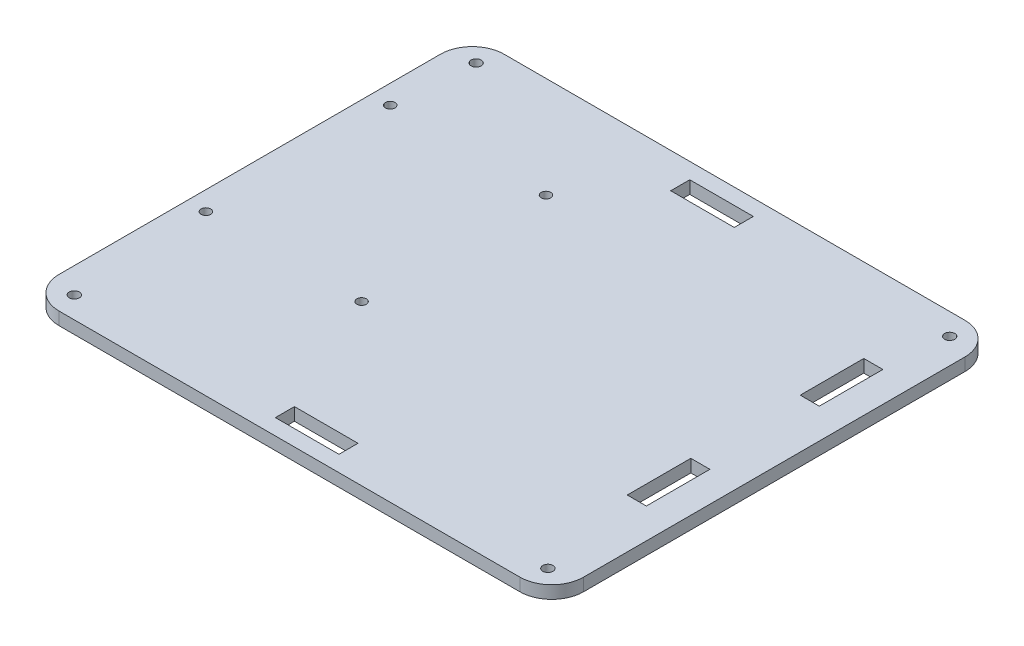
SolidWorks part; units mm, degrees
ref_plane "Front Plane" through (0, 0, 0) normal (0, 0, 1) x (1, 0, 0)
ref_plane "Top Plane" through (0, 0, 0) normal (0, 1, 0) x (1, 0, 0)
ref_plane "Right Plane" through (0, 0, 0) normal (1, 0, 0) x (0, 0, -1)
sketch "Sketch1" plane through (0, 0, 0) normal (0, 1, 0) x (1, 0, 0)
  line L1 (-82.5, 70) -> (82.5, 70)
  line L2 (-82.5, 70) -> (-82.5, -70)
  line L3 (-82.5, -70) -> (82.5, -70)
  line L4 (82.5, 70) -> (82.5, -70)
  line L5 (-82.5, 70) -> (82.5, -70) construction
  line L6 (-82.5, -70) -> (82.5, 70) construction
  point P0 (0, 0)
  dimension "D1" = 165
  dimension "D2" = 140
extrude "Boss-Extrude1" add sketch "Sketch1" along normal blind 4
sketch "Sketch2" plane through (0, 4, 0) normal (0, 1, 0) x (1, 0, 0)
  line L1 (-82.5, 70) -> (82.5, 70) construction
  line L2 (-82.5, 70) -> (-82.5, -70) construction
  line L3 (-82.5, -70) -> (82.5, -70) construction
  line L4 (82.5, 70) -> (82.5, -70) construction
  line L5 (-82.5, 70) -> (82.5, -70) construction
  line L6 (-82.5, -70) -> (82.5, 70) construction
  line L7 (74.5, -63.2121) -> (-74.5, -63.2121) construction
  line L8 (74.5, -63.2121) -> (74.5, 63.2121) construction
  line L9 (74.5, 63.2121) -> (-74.5, 63.2121) construction
  line L10 (-74.5, -63.2121) -> (-74.5, 63.2121) construction
  line L11 (74.5, -63.2121) -> (-74.5, 63.2121) construction
  line L12 (74.5, 63.2121) -> (-74.5, -63.2121) construction
  circle A0 centre (-74.5, 63.2121) radius 1.6
  circle A1 centre (-74.5, -63.2121) radius 1.6
  circle A2 centre (74.5, -63.2121) radius 1.6
  circle A3 centre (74.5, 63.2121) radius 1.6
  point P0 (0, 0)
  point P9 (0, 0)
  dimension "D1" = 3.2
  dimension "D2" = 8
extrude "Cut-Extrude1" cut sketch "Sketch2" against normal blind 10
fillet "Fillet1" radius 10 4 edges at (82.5, 2, -70) (82.5, 2, 70) (-82.5, 2, -70) (-82.5, 2, 70)
sketch "Sketch3" plane through (0, 4, 0) normal (0, 1, 0) x (1, 0, 0)
  line L1 (-80, 41.6892) -> (-24, 41.6892) construction
  line L2 (-80, 41.6892) -> (-80, -43.3108) construction
  line L3 (-80, -43.3108) -> (-24, -43.3108) construction
  line L4 (-24, 41.6892) -> (-24, -43.3108) construction
  line L5 (-80, 41.6892) -> (-24, -43.3108) construction
  line L6 (-80, -43.3108) -> (-24, 41.6892) construction
  line L7 (-76.5, 38.1892) -> (-27.5, 38.1892) construction
  line L8 (-76.5, 38.1892) -> (-76.5, -19.8108) construction
  line L9 (-76.5, -19.8108) -> (-27.5, -19.8108) construction
  line L10 (-27.5, 38.1892) -> (-27.5, -19.8108) construction
  line L11 (-76.5, 38.1892) -> (-27.5, -19.8108) construction
  line L12 (-76.5, -19.8108) -> (-27.5, 38.1892) construction
  circle A0 centre (-76.5, 38.1892) radius 1.5
  circle A1 centre (-27.5, 38.1892) radius 1.5
  circle A2 centre (-76.5, -19.8108) radius 1.5
  circle A3 centre (-27.5, -19.8108) radius 1.5
  point P0 (-52, -0.8108)
  point P5 (-52, 9.1892)
  dimension "D8" = 3
  dimension "D1" = 85
  dimension "D2" = 56
  dimension "D3" = 52
  dimension "D4" = 58
  dimension "D5" = 49
  dimension "D6" = 0
  dimension "D7" = 3.5
extrude "Cut-Extrude2" cut sketch "Sketch3" against normal blind 10
sketch "Sketch4" plane through (0, 4, 0) normal (0, 1, 0) x (1, 0, 0)
  line L1 (67, 43.681) -> (73, 43.681)
  line L2 (67, 43.681) -> (67, 23.681)
  line L3 (67, 23.681) -> (73, 23.681)
  line L4 (73, 43.681) -> (73, 23.681)
  line L5 (67, 43.681) -> (73, 23.681) construction
  line L6 (67, 23.681) -> (73, 43.681) construction
  line L7 (67, -10.7351) -> (73, -10.7351)
  line L8 (67, -10.7351) -> (67, -30.7351)
  line L9 (67, -30.7351) -> (73, -30.7351)
  line L10 (73, -10.7351) -> (73, -30.7351)
  line L11 (67, -10.7351) -> (73, -30.7351) construction
  line L12 (67, -30.7351) -> (73, -10.7351) construction
  line L13 (-9.4499, -59) -> (10.5501, -59)
  line L14 (-9.4499, -59) -> (-9.4499, -65)
  line L15 (-9.4499, -65) -> (10.5501, -65)
  line L16 (10.5501, -59) -> (10.5501, -65)
  line L17 (-9.4499, -59) -> (10.5501, -65) construction
  line L18 (-9.4499, -65) -> (10.5501, -59) construction
  line L19 (-9.0694, 65) -> (10.9306, 65)
  line L20 (-9.0694, 65) -> (-9.0694, 59)
  line L21 (-9.0694, 59) -> (10.9306, 59)
  line L22 (10.9306, 65) -> (10.9306, 59)
  line L23 (-9.0694, 65) -> (10.9306, 59) construction
  line L24 (-9.0694, 59) -> (10.9306, 65) construction
  point P0 (70, 33.681)
  point P5 (70, -20.7351)
  point P10 (0.5501, -62)
  point P15 (0.9306, 62)
  dimension "D1" = 6
  dimension "D2" = 20
  dimension "D3" = 20
  dimension "D4" = 20
  dimension "D5" = 6
  dimension "D6" = 6
  dimension "D7" = 20
  dimension "D8" = 6
  dimension "D9" = 70
  dimension "D10" = 70
  dimension "D11" = 62
  dimension "D12" = 62
extrude "Cut-Extrude3" cut sketch "Sketch4" against normal blind 10
